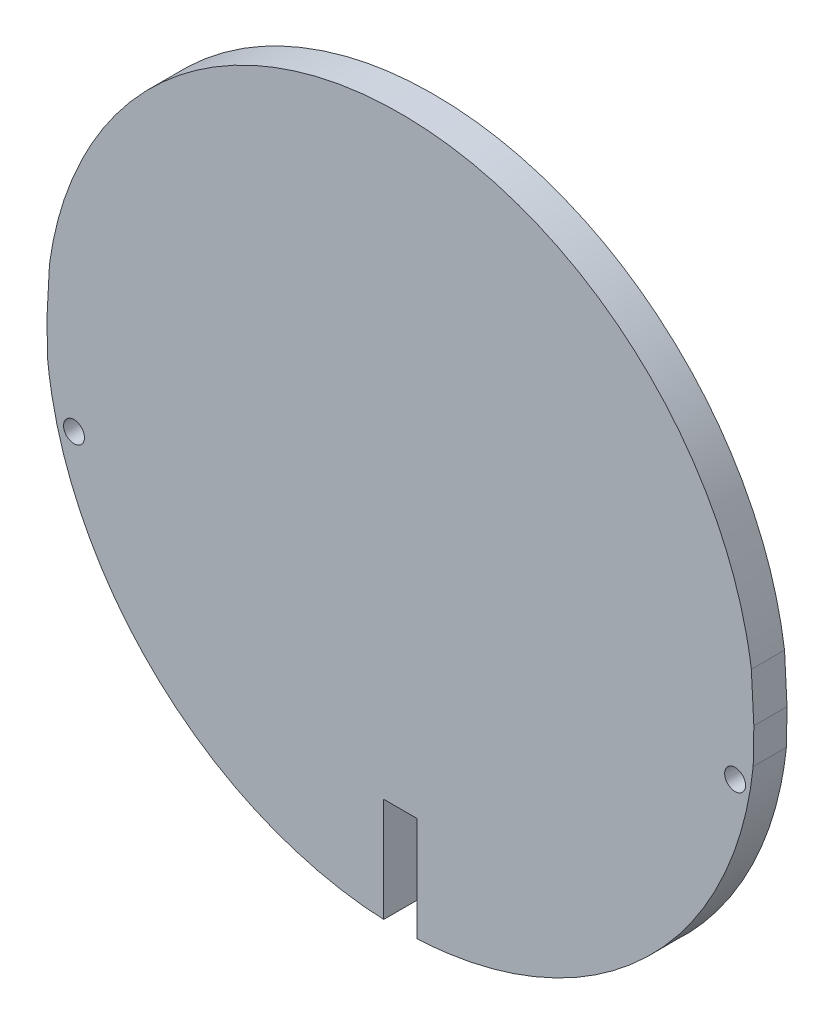
SolidWorks part; units mm, degrees
ref_plane "Front Plane" through (0, 0, 0) normal (0, 0, 1) x (1, 0, 0)
ref_plane "Top Plane" through (0, 0, 0) normal (0, 1, 0) x (1, 0, 0)
ref_plane "Right Plane" through (0, 0, 0) normal (1, 0, 0) x (0, 0, -1)
sketch "Sketch1" plane through (0, 0, 240) normal (0, 0, 1) x (1, 0, 0)
  line L8 (-33.7995, -0.0171) -> (-33.7401, -3.4188)
  line L9 (33.7402, -3.4188) -> (33.7996, -0.0171)
  line L10 (33.7996, -0.0171) -> (33.5604, 4.5461)
  line L11 (-33.5604, 4.5461) -> (-33.7995, -0.0171)
  line L12 (-33.7995, -0.0171) -> (-33.7401, -3.4188)
  line L13 (33.7402, -3.4188) -> (33.7996, -0.0171)
  line L14 (33.7996, -0.0171) -> (33.5604, 4.5461)
  line L15 (-33.5604, 4.5461) -> (-33.7995, -0.0171)
  spline S4 degree 3 poles (3584.2823, 1682.1592) (1891.8794, 981.7265) (-94.167, 198.9267) (-32.2457, -10.4865) (-31.7386, -11.9486) (-31.1278, -13.3816) (-30.6974, -14.3304) (-30.4704, -14.8019) (-29.2902, -17.1196) (-27.6449, -19.7403) (-25.6469, -22.1139) (-24.5884, -23.2589) (-24.2247, -23.6345) (-23.482, -24.3673) (-21.5901, -26.1504) (-18.7057, -28.3179) (-15.9808, -29.8236) (-14.107, -30.7477) (-13.1527, -31.1642) (-10.2562, -32.2793) (-7.778, -32.9883) (-5.2143, -33.4059) (-4.182, -33.5493) (-3.6613, -33.6093) (-2.1045, -33.752) (-1.0692, -33.7985) (2.0296, -33.8017) (4.086, -33.6221) (7.1551, -33.0587) (8.1781, -32.8207) (10.177, -32.2566) (11.1581, -31.9299) (14.0494, -30.8232) (15.9079, -29.9178) (18.1367, -28.5564) (18.5769, -28.2731) (19.4387, -27.6895) (20.707, -26.7866) (21.9036, -25.8034) (23.4386, -24.4244) (24.5444, -23.3394) (25.5786, -22.174) (26.2518, -21.3787) (26.581, -20.9708) (28.1709, -18.9029) (29.2697, -17.1529) (30.6789, -14.3959) (31.1088, -13.4548) (31.8841, -11.5261) (32.23, -10.5349) (99.7864, 216.9461) (-2290.3338, 992.2204) (3927.4834, -154.8641) knots -6.532325 -6.532325 -6.532325 -6.532325 0.0625 0.0625 0.09375 0.109375 0.109375 0.125 0.125 0.1875 0.21875 0.21875 0.234375 0.234375 0.25 0.3125 0.34375 0.34375 0.375 0.375 0.4375 0.453125 0.453125 0.46875 0.46875 0.5 0.5 0.5625 0.5625 0.59375 0.59375 0.625 0.625 0.6875 0.6875 0.703125 0.703125 0.71875 0.75 0.75 0.78125 0.796875 0.796875 0.8125 0.8125 0.875 0.875 0.90625 0.90625 0.9375 0.9375 8.025461 8.025461 8.025461 8.025461 only from (-33.7401, -3.4188) to (33.7402, -3.4188)
  spline S5 degree 3 poles (-3548.6792, -1753.5382) (-1588.5004, -923.6815) (94.7973, -181.1863) (31.8946, 11.4023) (31.3611, 12.8157) (30.7295, 14.1982) (30.2866, 15.113) (30.0537, 15.5679) (28.8457, 17.8053) (27.7362, 19.4878) (25.8529, 21.8475) (25.1886, 22.6067) (23.7865, 24.0699) (23.0451, 24.7766) (20.7523, 26.7783) (18.3111, 28.5582) (15.6406, 29.9959) (14.2667, 30.657) (13.8011, 30.8682) (12.8648, 31.268) (12.3937, 31.4568) (10.0246, 32.3475) (7.1153, 33.1595) (4.1023, 33.5707) (2.0702, 33.754) (1.0537, 33.7991) (-1.9787, 33.8028) (-4.4872, 33.5877) (-6.9715, 33.0844) (-7.9632, 32.8597) (-8.4594, 32.7353) (-9.9337, 32.3298) (-10.8974, 32.0168) (-13.7346, 30.9575) (-15.5548, 30.0922) (-17.7347, 28.7982) (-18.1659, 28.5288) (-19.0186, 27.9683) (-19.4392, 27.6779) (-20.674, 26.7832) (-21.4652, 26.1531) (-23.7487, 24.1676) (-25.1511, 22.7176) (-26.7425, 20.7348) (-27.0534, 20.3287) (-27.655, 19.5045) (-28.5257, 18.252) (-29.3043, 16.9523) (-30.7455, 14.2933) (-31.5513, 12.4411) (-32.5069, 9.533) (-32.7811, 8.5477) (-77.2289, -184.7715) (1567.6211, -755.0924) (-3962.2208, 280.2012) knots -6.201583 -6.201583 -6.201583 -6.201583 0.0625 0.0625 0.09375 0.109375 0.109375 0.125 0.125 0.1875 0.1875 0.21875 0.21875 0.25 0.25 0.3125 0.34375 0.34375 0.359375 0.359375 0.375 0.375 0.4375 0.46875 0.46875 0.5 0.5 0.5625 0.578125 0.578125 0.59375 0.59375 0.625 0.625 0.6875 0.6875 0.703125 0.703125 0.71875 0.71875 0.75 0.75 0.8125 0.8125 0.828125 0.828125 0.84375 0.875 0.875 0.9375 0.9375 0.96875 0.96875 7.021867 7.021867 7.021867 7.021867 only from (33.5604, 4.5461) to (-33.5604, 4.5461)
  spline S6 degree 3 poles (-33.7401, -3.4188) (-33.5219, -5.4967) (-33.1218, -7.5236) (-32.2457, -10.4865) (-31.7386, -11.9486) (-31.1278, -13.3816) (-30.6974, -14.3304) (-30.4704, -14.8019) (-29.2902, -17.1196) (-27.6449, -19.7403) (-25.6469, -22.1139) (-24.5884, -23.2589) (-24.2247, -23.6345) (-23.482, -24.3673) (-21.5901, -26.1504) (-18.7057, -28.3179) (-15.9808, -29.8236) (-14.107, -30.7477) (-13.1527, -31.1642) (-10.2562, -32.2793) (-7.778, -32.9883) (-5.2143, -33.4059) (-4.182, -33.5493) (-3.6613, -33.6093) (-2.1045, -33.752) (-1.0692, -33.7985) (2.0296, -33.8017) (4.086, -33.6221) (7.1551, -33.0587) (8.1781, -32.8207) (10.177, -32.2566) (11.1581, -31.9299) (14.0494, -30.8232) (15.9079, -29.9178) (18.1367, -28.5564) (18.5769, -28.2731) (19.4387, -27.6895) (20.707, -26.7866) (21.9036, -25.8034) (23.4386, -24.4244) (24.5444, -23.3394) (25.5786, -22.174) (26.2518, -21.3787) (26.581, -20.9708) (28.1709, -18.9029) (29.2697, -17.1529) (30.6789, -14.3959) (31.1088, -13.4548) (31.8841, -11.5261) (32.23, -10.5349) (33.1196, -7.5393) (33.5217, -5.4996) (33.7402, -3.4188) knots 0 0 0 0 0.0625 0.0625 0.09375 0.109375 0.109375 0.125 0.125 0.1875 0.21875 0.21875 0.234375 0.234375 0.25 0.3125 0.34375 0.34375 0.375 0.375 0.4375 0.453125 0.453125 0.46875 0.46875 0.5 0.5 0.5625 0.5625 0.59375 0.59375 0.625 0.625 0.6875 0.6875 0.703125 0.703125 0.71875 0.75 0.75 0.78125 0.796875 0.796875 0.8125 0.8125 0.875 0.875 0.90625 0.90625 0.9375 0.9375 1 1 1 1
  spline S7 degree 3 poles (33.5604, 4.5461) (33.2821, 6.5674) (32.8314, 8.5342) (31.8946, 11.4023) (31.3611, 12.8157) (30.7295, 14.1982) (30.2866, 15.113) (30.0537, 15.5679) (28.8457, 17.8053) (27.7362, 19.4878) (25.8529, 21.8475) (25.1886, 22.6067) (23.7865, 24.0699) (23.0451, 24.7766) (20.7523, 26.7783) (18.3111, 28.5582) (15.6406, 29.9959) (14.2667, 30.657) (13.8011, 30.8682) (12.8648, 31.268) (12.3937, 31.4568) (10.0246, 32.3475) (7.1153, 33.1595) (4.1023, 33.5707) (2.0702, 33.754) (1.0537, 33.7991) (-1.9787, 33.8028) (-4.4872, 33.5877) (-6.9715, 33.0844) (-7.9632, 32.8597) (-8.4594, 32.7353) (-9.9337, 32.3298) (-10.8974, 32.0168) (-13.7346, 30.9575) (-15.5548, 30.0922) (-17.7347, 28.7982) (-18.1659, 28.5288) (-19.0186, 27.9683) (-19.4392, 27.6779) (-20.674, 26.7832) (-21.4652, 26.1531) (-23.7487, 24.1676) (-25.1511, 22.7176) (-26.7425, 20.7348) (-27.0534, 20.3287) (-27.655, 19.5045) (-28.5257, 18.252) (-29.3043, 16.9523) (-30.7455, 14.2933) (-31.5513, 12.4411) (-32.5069, 9.533) (-32.7811, 8.5477) (-33.2376, 6.5619) (-33.4209, 5.5589) (-33.5604, 4.5461) knots 0 0 0 0 0.0625 0.0625 0.09375 0.109375 0.109375 0.125 0.125 0.1875 0.1875 0.21875 0.21875 0.25 0.25 0.3125 0.34375 0.34375 0.359375 0.359375 0.375 0.375 0.4375 0.46875 0.46875 0.5 0.5 0.5625 0.578125 0.578125 0.59375 0.59375 0.625 0.625 0.6875 0.6875 0.703125 0.703125 0.71875 0.71875 0.75 0.75 0.8125 0.8125 0.828125 0.828125 0.84375 0.875 0.875 0.9375 0.9375 0.96875 0.96875 1 1 1 1
  dimension "D1" = 1
extrude "Boss-Extrude1" add sketch "Sketch1" along normal blind 3.175
sketch "Sketch4" plane through (0, 0, 243.175) normal (0, 0, 1) x (1, 0, 0)
  circle A0 centre (32.0093, -5.359) radius 1 construction
  circle A1 centre (-31.2161, -8.1644) radius 1 construction
  circle A2 centre (32.0093, -5.359) radius 1
  circle A3 centre (-31.2161, -8.1644) radius 1
extrude "Cut-Extrude2" cut sketch "Sketch4" against normal blind 3.175
sketch "Sketch5" plane through (0, 0, 243.175) normal (0, 0, 1) x (1, 0, 0)
  line L0 (-1.6006, -23.7996) -> (-1.6006, -34.7702) construction
  line L1 (-1.6006, -23.7996) -> (1.5744, -23.7996) construction
  line L2 (1.5744, -34.7702) -> (1.5744, -23.7996) construction
  line L3 (-1.6006, -34.7702) -> (1.5744, -34.7702) construction
  line L4 (-1.6006, -23.7996) -> (-1.6006, -34.7702)
  line L5 (-1.6006, -23.7996) -> (1.5744, -23.7996)
  line L6 (1.5744, -34.7702) -> (1.5744, -23.7996)
  line L7 (-1.6006, -34.7702) -> (1.5744, -34.7702)
extrude "Cut-Extrude3" cut sketch "Sketch5" against normal through all
